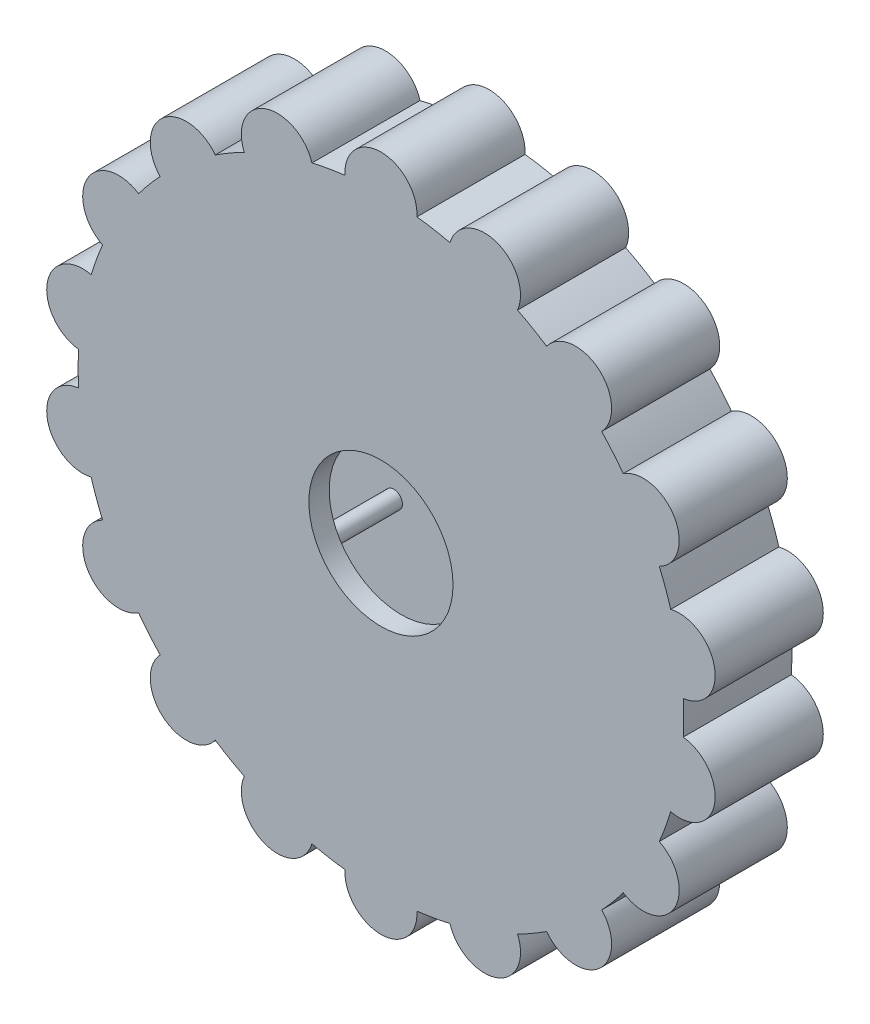
SolidWorks part; units mm, degrees
material "Silicon Rubber"
ref_plane "Front" through (0, 0, 0) normal (0, 0, 1) x (1, 0, 0)
ref_plane "Top" through (0, 0, 0) normal (0, 1, 0) x (1, 0, 0)
ref_plane "Right" through (0, 0, 0) normal (1, 0, 0) x (0, 0, -1)
sketch "Sketch6" plane through (0, 0, 0) normal (0, 0, 1) x (1, 0, 0)
  circle A0 centre (0, 0) radius 53.34
  circle A18 centre (0, 53.34) radius 6.35
  circle A20 centre (18.2434, 50.1232) radius 6.35
  circle A21 centre (34.2863, 40.8608) radius 6.35
  circle A22 centre (46.1938, 26.67) radius 6.35
  circle A23 centre (52.5296, 9.2624) radius 6.35
  circle A24 centre (52.5296, -9.2624) radius 6.35
  circle A25 centre (46.1938, -26.67) radius 6.35
  circle A26 centre (34.2863, -40.8608) radius 6.35
  circle A27 centre (18.2434, -50.1232) radius 6.35
  circle A28 centre (0, -53.34) radius 6.35
  circle A29 centre (-18.2434, -50.1232) radius 6.35
  circle A30 centre (-34.2863, -40.8608) radius 6.35
  circle A31 centre (-46.1938, -26.67) radius 6.35
  circle A32 centre (-52.5296, -9.2624) radius 6.35
  circle A33 centre (-52.5296, 9.2624) radius 6.35
  circle A34 centre (-46.1938, 26.67) radius 6.35
  circle A35 centre (-34.2863, 40.8608) radius 6.35
  circle A36 centre (-18.2434, 50.1232) radius 6.35
  point P49 (0, 0)
  dimension "D1" = 106.68
  dimension "D3" = 18
  dimension "D4" = 12.7
extrude "Boss-Extrude1" add sketch "Sketch6" along normal blind 19.05 contours A36 A0 A35 A34 A33 A32 A31 A30 A29 A28 A27 A26 A25 A24 A23 A22 A21 A20 A18 | A0 A35 | A0 A35 | A0 A36 | A0 A36 | A0 A18 | A0 A18 | A0 A20 | A0 A20 | A0 A21 | A0 A21 | A0 A22 | A0 A22 | A0 A23 | A0 A23 | A0 A24 | A0 A25 | A0 A26 | A0 A25 | A0 A27 | A0 A27 | A0 A26 | A0 A34 | A0 A33 | A0 A32 | A0 A30 | A0 A29 | A0 A28
sketch "Sketch7" plane through (0, 0, 0) normal (0, 0, -1) x (-1, 0, 0)
  circle A0 centre (0, 0) radius 50.8
  dimension "D1" = 101.6
ref_plane "Plane1" through (0, 0, 9.525) normal (0, 0, 1) x (1, 0, 0)
sketch "Sketch10" plane through (0, 0, 9.525) normal (0, 0, 1) x (1, 0, 0)
  line L0 (0, 0) -> (0, 78.8856) construction
  circle A0 centre (0, 44.45) radius 2.54
  circle A1 centre (38.4948, 22.225) radius 2.54
  circle A2 centre (38.4948, -22.225) radius 2.54
  circle A3 centre (0, -44.45) radius 2.54
  circle A4 centre (-38.4948, -22.225) radius 2.54
  circle A5 centre (-38.4948, 22.225) radius 2.54
  circle A6 centre (0, 0) radius 50.8
  circle A7 centre (0, 15.24) radius 1.524
  circle A8 centre (13.1982, -7.62) radius 1.524
  circle A9 centre (-13.1982, -7.62) radius 1.524
  point P18 (0, 0)
  point P26 (0, 0)
  dimension "D1" = 5.08
  dimension "D4" = 101.6
  dimension "D6" = 3.048
  dimension "D2" = 44.45
  dimension "D5" = 15.24
  dimension "D3" = 6
  dimension "D7" = 3
extrude "Cut-Extrude3" cut sketch "Sketch10" against normal mid plane 11.8872
sketch "Sketch11" plane through (0, 0, 19.05) normal (0, 0, 1) x (1, 0, 0)
  circle A0 centre (0, 0) radius 12.7
  dimension "D1" = 25.4
extrude "Cut-Extrude4" cut sketch "Sketch11" against normal up to surface (9.525 mm away) contours A0 up to plane "Plane1"
